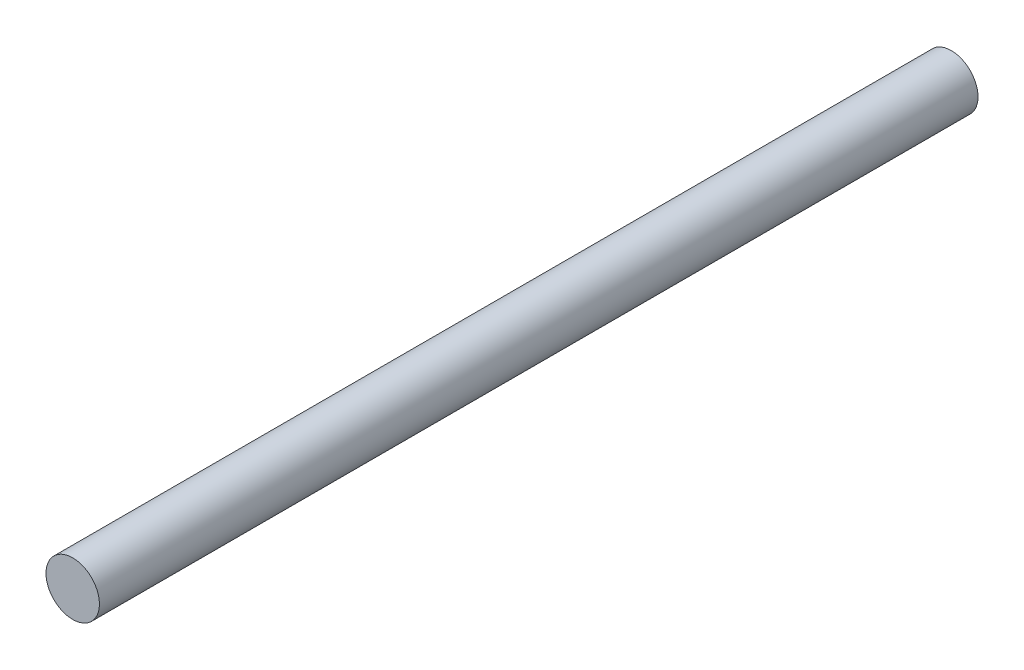
SolidWorks part; units mm, degrees
material "铸造合金钢"
ref_plane "前视基准面" through (0, 0, 0) normal (0, 0, 1) x (1, 0, 0)
ref_plane "上视基准面" through (0, 0, 0) normal (0, 1, 0) x (1, 0, 0)
ref_plane "右视基准面" through (0, 0, 0) normal (1, 0, 0) x (0, 0, -1)
sketch "草图7" plane through (0, 0, 0) normal (0, 1, 0) x (1, 0, 0)
  line L0 (0, 60) -> (0, -500) construction
  circle A0 centre (0, -500) radius 15
  circle A1 centre (0, -500) radius 35
  dimension "D1" = 30
  dimension "D3" = 70
  dimension "D2" = 500
ref_plane "基准面3" through (0, 0, -280) normal (0, 0, 1) x (1, 0, 0)
sketch "草图5" plane through (0, 0, -280) normal (0, 0, 1) x (1, 0, 0)
  circle A0 centre (0, 0) radius 22.5
  dimension "D1" = 45
extrude "凸台-拉伸1" add sketch "草图7" along normal mid plane 30
extrude "凸台-拉伸2" add sketch "草图5" along normal up to surface (753.1905 mm away)
ref_plane "基准面4" through (0, 0, 500) normal (0, 0, 1) x (1, 0, 0)
sketch "草图8" plane through (0, 0, 0) normal (0, 1, 0) x (1, 0, 0)
  line L1 (-95.1406, -595.3502) -> (90.1544, -595.3502)
  line L2 (-95.1406, -595.3502) -> (-95.1406, -460)
  line L3 (-95.1406, -460) -> (90.1544, -460)
  line L4 (90.1544, -595.3502) -> (90.1544, -460)
  circle A0 centre (0, -500) radius 15 construction
  dimension "D1" = 40
extrude "切除-拉伸1" cut sketch "草图8" against normal mid plane 50
